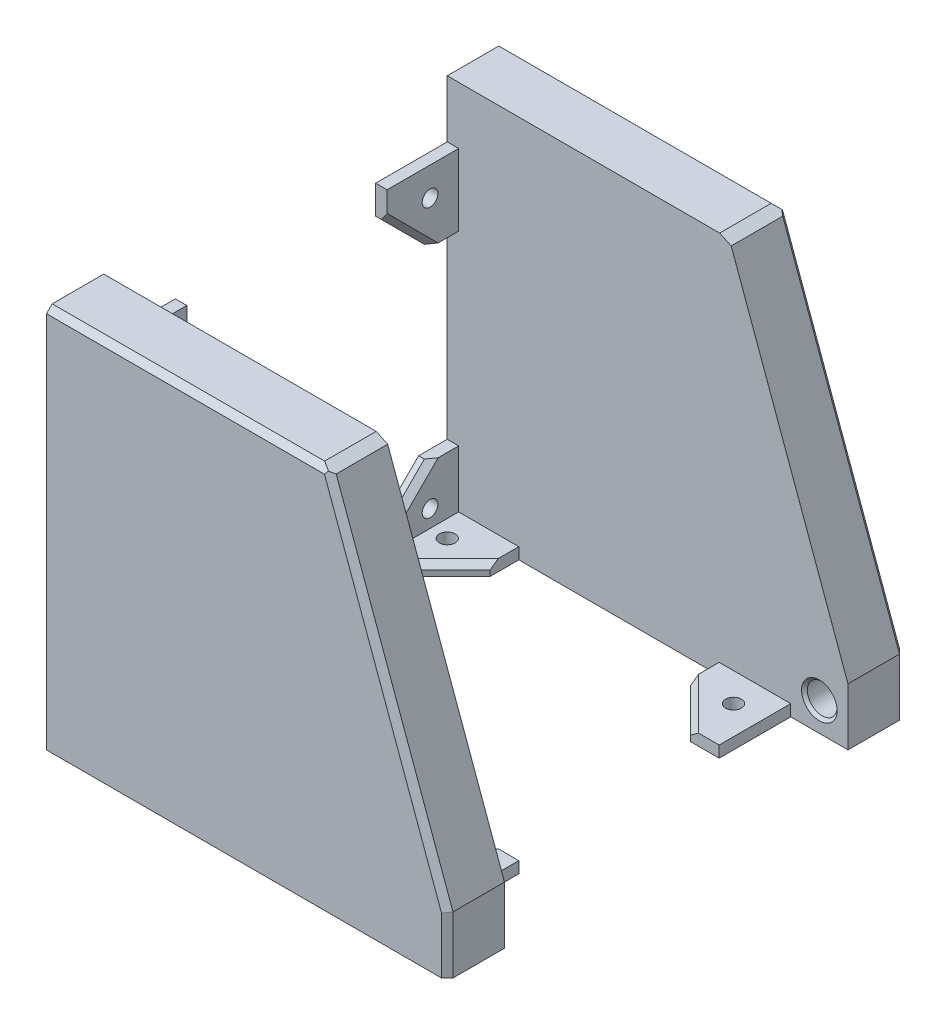
SolidWorks part; units mm, degrees
ref_plane "Front Plane" through (0, 0, 0) normal (0, 0, 1) x (1, 0, 0)
ref_plane "Top Plane" through (0, 0, 0) normal (0, 1, 0) x (1, 0, 0)
ref_plane "Right Plane" through (0, 0, 0) normal (1, 0, 0) x (0, 0, -1)
sketch "Sketch1" plane through (0, 0, 0) normal (0, 0, 1) x (1, 0, 0)
  line L0 (-5, 5) -> (-22.101, 51.9846)
  line L1 (-5, -5) -> (5, -5)
  line L2 (-5, -5) -> (-5, 5)
  line L3 (-5, 5) -> (5, 5)
  line L4 (5, -5) -> (5, 5)
  line L5 (-5, -5) -> (5, 5) construction
  line L6 (-5, 5) -> (5, -5) construction
  line L7 (5, 5) -> (-12.101, 51.9846)
  line L8 (-12.101, 51.9846) -> (-15.7407, 61.9846)
  line L9 (-22.101, 51.9846) -> (-32.101, 51.9846)
  line L10 (-22.101, 51.9846) -> (-22.101, 61.9846)
  line L11 (-22.101, 61.9846) -> (-32.101, 61.9846)
  line L12 (-32.101, 51.9846) -> (-32.101, 61.9846)
  line L13 (-15.7407, 61.9846) -> (-22.101, 61.9846)
  line L14 (-65, -5) -> (-5, -5)
  line L18 (-65, -5) -> (-65, 51.9846)
  line L22 (-65, 51.9846) -> (-65, 61.9846)
  line L23 (-65, 61.9846) -> (-32.101, 61.9846)
  line L24 (-32.101, 51.9846) -> (-32.101, 61.9846)
  point P0 (0, 0)
  dimension "D1" = 10
  dimension "D2" = 10
  dimension "D3" = 10
  dimension "D4" = 10
extrude "Boss-Extrude1" add sketch "Sketch1" along normal blind 80
sketch "Sketch2" plane through (5, 0, 0) normal (1, 0, 0) x (0, 0, -1)
  line L0 (-80, -5) -> (0, -5) construction
  line L1 (-80, -5) -> (-70, -5)
  line L2 (-80, 61.9846) -> (0, 61.9846) construction
  line L3 (-70, -5) -> (-10, -5)
  line L4 (-70, -5) -> (-70, 61.9846)
  line L5 (-70, 61.9846) -> (-10, 61.9846)
  line L6 (-10, -5) -> (-10, 61.9846)
  line M3 (0, 5) -> (-80, 5)
  line M5 (-80, -5) -> (0, -5)
  dimension "D1" = 10
  dimension "D2" = 60
extrude "Cut-Extrude3" cut sketch "Sketch2" against normal up to surface (70 mm away) contours L6 L5 L4 M3 | L6 L4 M5 M3 up to face at (-65, 28.4923, 40)
sketch "Sketch4" plane through (0, 0, 10) normal (0, 0, 1) x (1, 0, 0)
  circle A0 centre (0, 0) radius 2.6
extrude "Cut-Extrude4" cut sketch "Sketch4" against normal blind 5 and the other way offset from surface (65 mm away) 5 other way up to face at (-27.1481, 23.7939, 70)
sketch "Sketch6" plane through (0, -5, 0) normal (0, -1, 0) x (1, 0, 0)
  line L0 (-65, 10) -> (5, 10) construction
  line L1 (-65, 70) -> (-52.5, 70)
  line L2 (-65, 70) -> (-65, 57.5)
  line L3 (-65, 57.5) -> (-52.5, 57.5)
  line L4 (-52.5, 70) -> (-52.5, 57.5)
  line L5 (-65, 10) -> (-52.5, 10)
  line L6 (-65, 10) -> (-65, 22.5)
  line L7 (-65, 22.5) -> (-52.5, 22.5)
  line L8 (-52.5, 10) -> (-52.5, 22.5)
  line L9 (-52.5, 70) -> (-17.5, 70)
  line L10 (-65, 70) -> (5, 70) construction
  line L11 (-52.5, 10) -> (-17.5, 10)
  line L13 (-17.5, 10) -> (-5, 10)
  line L14 (-17.5, 10) -> (-17.5, 22.5)
  line L15 (-17.5, 22.5) -> (-5, 22.5)
  line L16 (-5, 10) -> (-5, 22.5)
  line L17 (-17.5, 70) -> (-5, 70)
  line L18 (-17.5, 70) -> (-17.5, 57.5)
  line L19 (-17.5, 57.5) -> (-5, 57.5)
  line L20 (-5, 70) -> (-5, 57.5)
  line M7 (-65, 70) -> (5, 70)
  dimension "D1" = 12.5
  dimension "D2" = 12.5
  dimension "D3" = 12.5
  dimension "D4" = 12.5
extrude "Boss-Extrude2" add sketch "Sketch6" against normal blind 2 contours L20 L18 L19 M7 | L4 L2 L3 M7 | L5 L8 L7 L6 | L13 L16 L15 L14
chamfer "Chamfer1" distance 7.5 angle 45 2 edges at (-17.5, -4, 22.5) (-52.5, -4, 22.5)
chamfer "Chamfer2" distance 7.5 angle 45 2 edges at (-17.5, -4, 57.5) (-52.5, -4, 57.5)
sketch "Sketch7" plane through (0, -3, 0) normal (0, 1, 0) x (1, 0, 0)
  circle A0 centre (-60, -15) radius 1.375
  circle A1 centre (-10, -15) radius 1.375
  circle A2 centre (-10, -65) radius 1.375
  circle A3 centre (-60, -65) radius 1.375
  point P0 (-60, -22.5)
  point P1 (-10, -22.5)
  point P3 (-10, -57.5)
  point P5 (-60, -57.5)
extrude "Cut-Extrude5" cut sketch "Sketch7" against normal up to surface (2 mm away) up to face at (-28.3333, -5, 13.3333)
chamfer "Chamfer3" distance 1 angle 45 3 edges at (-40.3704, 61.9846, 0) (5, 0, 0) (-5.3704, 33.4923, 0)
chamfer "Chamfer4" distance 1 angle 45 3 edges at (5, 0, 80) (-5.3704, 33.4923, 80) (-40.3704, 61.9846, 80)
chamfer "Chamfer5" distance 1 angle 45 2 edges at (-13.75, -3, 61.25) (-56.25, -3, 61.25)
chamfer "Chamfer6" distance 1 angle 45 2 edges at (-13.75, -3, 18.75) (-56.25, -3, 18.75)
chamfer "Chamfer7" distance 0.5 angle 45 1 edges at (-2.6, 0, 70)
chamfer "Chamfer8" distance 0.5 angle 45 1 edges at (-2.6, 0, 10)
chamfer "Chamfer9" distance 1 angle 45 1 edges at (-15.7407, 61.9846, 74.5)
chamfer "Chamfer10" distance 1 angle 45 1 edges at (-15.7407, 61.9846, 5.5)
sketch "Sketch9" plane through (0, -3, 0) normal (0, 1, 0) x (1, 0, 0)
  line L0 (-65, -22.5) -> (-61.4142, -22.5) construction
  line L1 (-65, -10) -> (-63, -10)
  line L2 (-65, -10) -> (-65, -22.5)
  line L3 (-65, -22.5) -> (-63, -22.5)
  line L4 (-63, -10) -> (-63, -22.5)
  line L5 (-65, -57.5) -> (-61.4142, -57.5) construction
  line L6 (-65, -70) -> (-63, -70)
  line L7 (-65, -70) -> (-65, -57.5)
  line L8 (-65, -57.5) -> (-63, -57.5)
  line L9 (-63, -70) -> (-63, -57.5)
  dimension "D1" = 2
extrude "Boss-Extrude3" add sketch "Sketch9" along normal blind 10
chamfer "Chamfer11" distance 7.5 angle 45 1 edges at (-64, 7, 22.5)
chamfer "Chamfer12" distance 7.5 angle 45 1 edges at (-64, 7, 57.5)
chamfer "Chamfer13" distance 1 angle 45 1 edges at (-63, 3.25, 18.75)
chamfer "Chamfer14" distance 1 angle 45 1 edges at (-63, 3.25, 61.25)
sketch "Sketch11" plane through (0, 0, 70) normal (0, 0, -1) x (-1, 0, 0)
  line L0 (65, 61.9846) -> (65, 51.9846)
  line L1 (65, 7) -> (65, 61.9846) construction
  line L3 (65, 51.9846) -> (63, 51.9846)
  line L4 (65, 51.9846) -> (65, 39.4846)
  line L5 (65, 39.4846) -> (63, 39.4846)
  line L6 (63, 51.9846) -> (63, 39.4846)
  line M7 (65, 7) -> (65, 61.9846)
  dimension "D1" = 2
  dimension "D2" = 12.5
extrude "Boss-Extrude4" add sketch "Sketch11" along normal blind 12.5 contours L3 L6 L5 M7
sketch "Sketch12" plane through (0, 0, 10) normal (0, 0, 1) x (1, 0, 0)
  line L0 (-65, 61.9846) -> (-65, 51.9846)
  line L1 (-65, 7) -> (-65, 61.9846) construction
  line L3 (-65, 51.9846) -> (-63, 51.9846)
  line L4 (-65, 51.9846) -> (-65, 39.4846)
  line L5 (-65, 39.4846) -> (-63, 39.4846)
  line L6 (-63, 51.9846) -> (-63, 39.4846)
  line M16 (-65, 61.9846) -> (-65, 7)
  dimension "D1" = 2
  dimension "D2" = 12.5
extrude "Boss-Extrude5" add sketch "Sketch12" along normal blind 12.5 contours L6 L3 L5 M16
chamfer "Chamfer15" distance 7.5 angle 45 1 edges at (-64, 39.4846, 22.5)
chamfer "Chamfer16" distance 7.5 angle 45 1 edges at (-64, 39.4846, 57.5)
chamfer "Chamfer17" distance 1 angle 45 1 edges at (-63, 43.2346, 61.25)
chamfer "Chamfer18" distance 1 angle 45 1 edges at (-63, 43.2346, 18.75)
sketch "Sketch10" plane through (-63, 0, 0) normal (1, 0, 0) x (0, 0, -1)
  line L0 (-70, -3) -> (-65, -3)
  line L1 (-70, -3) -> (-57.5, -3) construction
  line L2 (-65, -3) -> (-65, 0)
  line L3 (-10, -3) -> (-15, -3)
  line L4 (-10, -3) -> (-22.5, -3) construction
  line L5 (-15, -3) -> (-15, 0)
  line L6 (-65, 51.9846) -> (-65, 46.9846)
  line L7 (-57.5, 51.9846) -> (-70, 51.9846) construction
  line L8 (-15, 51.9846) -> (-15, 46.9846)
  line L9 (-22.5, 51.9846) -> (-10, 51.9846) construction
  circle A0 centre (-65, 0) radius 1.375
  circle A1 centre (-15, 0) radius 1.375
  circle A2 centre (-65, 46.9846) radius 1.375
  circle A3 centre (-15, 46.9846) radius 1.375
extrude "Cut-Extrude6" cut sketch "Sketch10" against normal up to surface (2 mm away) up to face at (-65, 32.1828, 67.6154)
